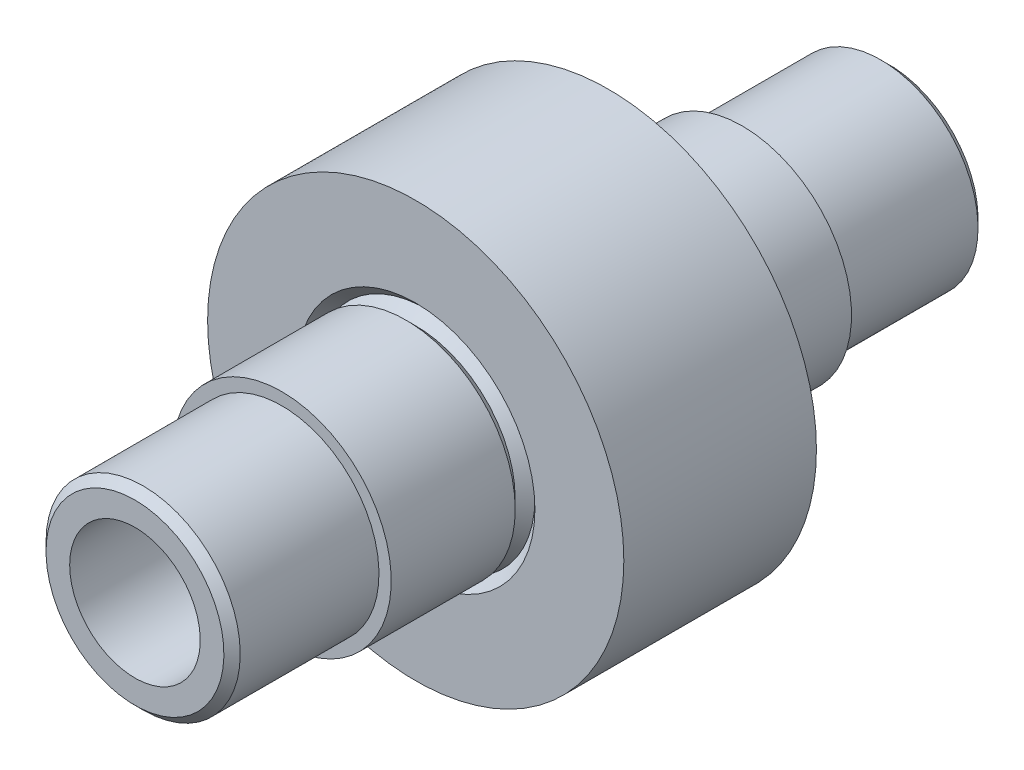
SolidWorks part; units mm, degrees
ref_plane "前视基准面" through (0, 0, 0) normal (0, 0, 1) x (1, 0, 0)
ref_plane "上视基准面" through (0, 0, 0) normal (0, 1, 0) x (1, 0, 0)
ref_plane "右视基准面" through (0, 0, 0) normal (1, 0, 0) x (0, 0, -1)
sketch "草图1" plane through (0, 0, 0) normal (1, 0, 0) x (0, 0, -1)
  line L0 (-25.6494, 0) -> (28.1258, 0) construction
  line L1 (-23.1, 0) -> (-23.1, 5.95)
  line L2 (-23.1, 5.95) -> (-14.1, 5.95)
  line L3 (-14.1, 5.95) -> (-14.1, 6.7) construction
  line L5 (-5.9, 6.7) -> (-5.9, 14)
  line L6 (-5.9, 14) -> (5.9, 14)
  line L7 (0, 14) -> (0, 0) construction
  line L8 (5.9, 6.7) -> (5.9, 14)
  line L9 (14.1, 6.7) -> (5.9, 6.7)
  line L10 (14.1, 5.95) -> (14.1, 6.7) construction
  line L11 (23.1, 5.95) -> (14.1, 5.95)
  line L12 (23.1, 0) -> (23.1, 5.95)
  line L13 (-23.1, 0) -> (23.1, 0)
  line L15 (-14.1, 6.7) -> (-5.9, 6.7) construction
  line L19 (14.1, 6.7) -> (14.1, 5.95)
  line L20 (-5.9, 6.7) -> (-14.1, 6.7)
  line L21 (-14.1, 6.7) -> (-14.1, 5.95)
  dimension "D1" = 5.95
  dimension "D2" = 11.8
  dimension "D3" = 14
  dimension "D4" = 9
  dimension "D5" = 8.2
  dimension "D6" = 6.7
  dimension "D7" = 46.2
revolve "旋转1" add sketch "草图1" angle 360 about L13
sketch "草图2" plane through (0, 0, 5.9) normal (0, 0, 1) x (1, 0, 0)
  line L0 (0, 0) -> (0, 10.5) construction
  circle A0 centre (0, 0) radius 10.5 construction
  circle A1 centre (0, 10.5) radius 1.5
  circle A2 centre (0, 0) radius 10.5 construction
  circle A3 centre (10.5, 0) radius 1.5
  circle A4 centre (0, 0) radius 10.5 construction
  circle A5 centre (0, -10.5) radius 1.5
  circle A6 centre (0, 0) radius 10.5 construction
  circle A7 centre (-10.5, 0) radius 1.5
  dimension "D1" = 21
  dimension "D2" = 3
  dimension "D3" = 4
extrude "切除-拉伸1" cut sketch "草图2" against normal through all
sketch "草图4" plane through (0, 0, -5.9) normal (0, 0, -1) x (-1, 0, 0)
  circle A0 centre (0, 0) radius 12.75
  circle A1 centre (0, 0) radius 14 construction
  circle A2 centre (0, 0) radius 14
  dimension "D1" = 25.5
extrude "切除-拉伸4" cut sketch "草图4" against normal through all
sketch "草图5" plane through (0, 0, -5.9) normal (0, 0, -1) x (-1, 0, 0)
  line L0 (-9.2687, 3.6181) -> (-8.332, 3.2525)
  line L1 (-3.6181, 9.2687) -> (-3.2525, 8.332)
  line L8 (3.6181, 9.2687) -> (3.2525, 8.332)
  line L9 (9.2687, 3.6181) -> (8.332, 3.2525)
  line L10 (9.2687, -3.6181) -> (8.332, -3.2525)
  line L11 (3.6181, -9.2687) -> (3.2525, -8.332)
  line L12 (-3.6181, -9.2687) -> (-3.2525, -8.332)
  line L13 (-9.2687, -3.6181) -> (-8.332, -3.2525)
  circle A2 centre (-10.5, 0) radius 1.5 construction
  circle A4 centre (0, 10.5) radius 1.5 construction
  arc A6 (-3.7191, 7.083) -> (-7.083, 3.7191) centre (0, 0) ccw
  arc A7 (-5.0046, 9.7956) -> (-9.7956, 5.0046) centre (0, 0) ccw
  arc A14 (-8.332, 3.2525) -> (-7.083, 3.7191) centre (-7.9683, 4.184) ccw
  arc A15 (-9.2687, 3.6181) -> (-9.7956, 5.0046) centre (-8.9051, 4.5497) cw
  arc A16 (-3.2525, 8.332) -> (-3.7191, 7.083) centre (-4.184, 7.9683) cw
  arc A17 (-3.6181, 9.2687) -> (-5.0046, 9.7956) centre (-4.5497, 8.9051) ccw
  arc A18 (3.6181, 9.2687) -> (5.0046, 9.7956) centre (4.5497, 8.9051) cw
  arc A19 (3.2525, 8.332) -> (3.7191, 7.083) centre (4.184, 7.9683) ccw
  arc A20 (7.083, 3.7191) -> (3.7191, 7.083) centre (0, 0) ccw
  arc A21 (8.332, 3.2525) -> (7.083, 3.7191) centre (7.9683, 4.184) cw
  arc A22 (9.2687, 3.6181) -> (9.7956, 5.0046) centre (8.9051, 4.5497) ccw
  arc A23 (9.7956, 5.0046) -> (5.0046, 9.7956) centre (0, 0) ccw
  arc A24 (9.2687, -3.6181) -> (9.7956, -5.0046) centre (8.9051, -4.5497) cw
  arc A25 (8.332, -3.2525) -> (7.083, -3.7191) centre (7.9683, -4.184) ccw
  arc A26 (3.7191, -7.083) -> (7.083, -3.7191) centre (0, 0) ccw
  arc A27 (3.2525, -8.332) -> (3.7191, -7.083) centre (4.184, -7.9683) cw
  arc A28 (3.6181, -9.2687) -> (5.0046, -9.7956) centre (4.5497, -8.9051) ccw
  arc A29 (5.0046, -9.7956) -> (9.7956, -5.0046) centre (0, 0) ccw
  arc A30 (-3.6181, -9.2687) -> (-5.0046, -9.7956) centre (-4.5497, -8.9051) cw
  arc A31 (-3.2525, -8.332) -> (-3.7191, -7.083) centre (-4.184, -7.9683) ccw
  arc A32 (-7.083, -3.7191) -> (-3.7191, -7.083) centre (0, 0) ccw
  arc A33 (-8.332, -3.2525) -> (-7.083, -3.7191) centre (-7.9683, -4.184) cw
  arc A34 (-9.2687, -3.6181) -> (-9.7956, -5.0046) centre (-8.9051, -4.5497) ccw
  arc A35 (-9.7956, -5.0046) -> (-5.0046, -9.7956) centre (0, 0) ccw
  point P23 (0, 0)
  point P25 (0, 0)
  point P27 (-10.247, 4)
  point P32 (-4, 10.247)
  point P44 (0, 0)
  point P57 (0, 0)
  point P63 (0, 0)
  dimension "D3" = 11
  dimension "D4" = 8
  dimension "D6" = 1
  dimension "D1" = 4
  dimension "D2" = 4
extrude "切除-拉伸5" cut sketch "草图5" against normal through all
sketch "草图6" plane through (0, 0, -23.1) normal (0, 0, -1) x (-1, 0, 0)
  circle A0 centre (0, 0) radius 4
  dimension "D1" = 8
extrude "切除-拉伸6" cut sketch "草图6" against normal through all
sketch "草图7" plane through (0, 0, -5.9) normal (0, 0, -1) x (-1, 0, 0)
  circle A1 centre (0, 0) radius 12.75
  circle A2 centre (0, 0) radius 12.75
  circle A5 centre (0, 0) radius 6.7
  circle A6 centre (0, 0) radius 6.7
  dimension "D1" = 0
  dimension "D2" = 0
extrude "凸台-拉伸1" add sketch "草图7" against normal up to surface (11.8 mm away) up to face at (0, -6.7, 5.9)
sketch "草图8" plane through (0, 0, 0) normal (1, 0, 0) x (0, 0, -1)
  line L0 (-6.5021, 6.7) -> (-5.9, 6.0932)
  line L1 (-5.9, 6.7) -> (-14.1, 6.7) construction
  line L2 (-5.9, 12.75) -> (-5.9, -12.75) construction
  line L3 (-5.9, 6.0932) -> (-5.2948, 6.7)
  line L4 (-5.2948, 6.7) -> (-5.9, 7.3037)
  line L5 (0, 0) -> (13.1023, 0) construction
  line L6 (-6.5021, 6.7) -> (-5.9, 7.3037)
  line L7 (0, 0) -> (0, 5.093) construction
  line L8 (6.5021, 6.7) -> (5.9, 7.3037)
  line L9 (5.2948, 6.7) -> (5.9, 7.3037)
  line L10 (5.9, 6.0932) -> (5.2948, 6.7)
  line L11 (6.5021, 6.7) -> (5.9, 6.0932)
revolve "切除-旋转1" cut sketch "草图8" angle 360 about L5
chamfer "倒角1" distance 0.5 angle 45 2 edges at (0, -5.95, -23.1) (0, -5.95, 23.1)
move or copy body "实体-移动/复制1" [suppressed] bodies to move or copy 113
